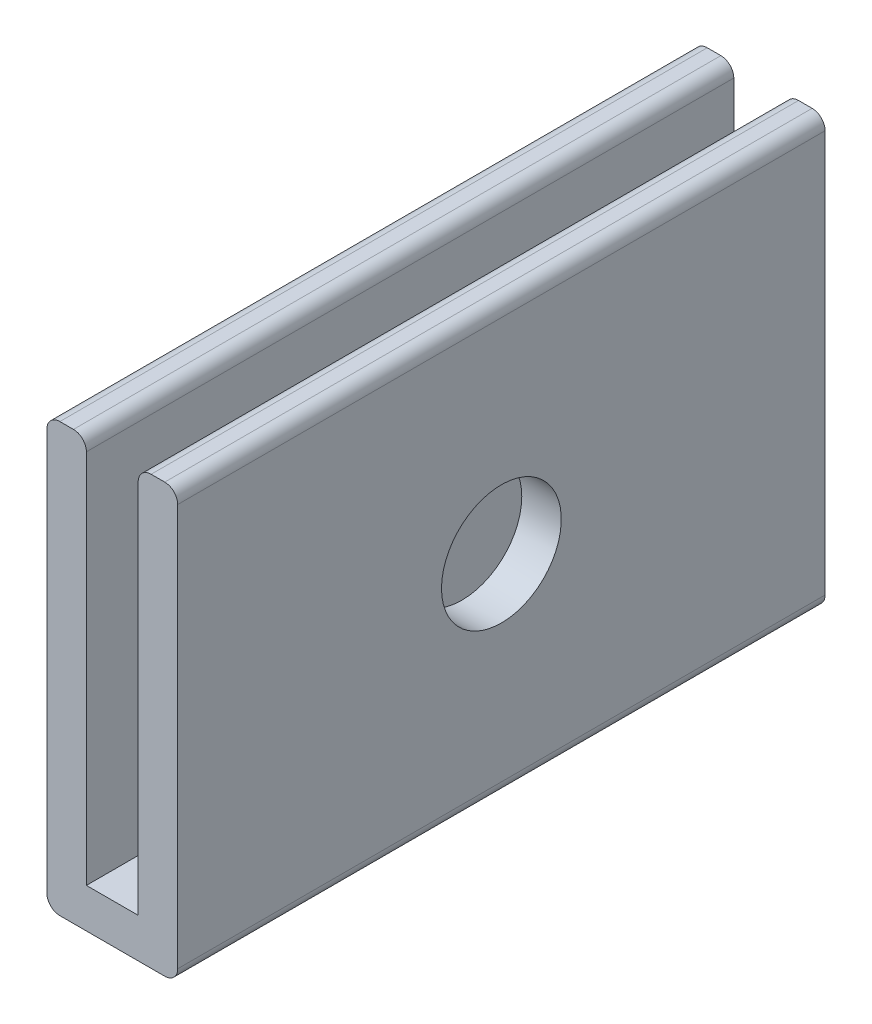
SolidWorks part; units mm, degrees
ref_plane "Front Plane" through (0, 0, 0) normal (0, 0, 1) x (1, 0, 0)
ref_plane "Top Plane" through (0, 0, 0) normal (0, 1, 0) x (1, 0, 0)
ref_plane "Right Plane" through (0, 0, 0) normal (1, 0, 0) x (0, 0, -1)
sketch "Sketch1" plane through (0, 0, 0) normal (0, 0, 1) x (1, 0, 0)
  line L17 (3.22, 13.22) -> (3.64, 13.22)
  line L18 (1.22, 1.22) -> (2.82, 1.22)
  line L19 (0.4, 0) -> (3.64, 0)
  line L20 (0, 0.4) -> (0, 12.82)
  line L21 (0.4, 13.22) -> (0.82, 13.22)
  line L22 (4.04, 0.4) -> (4.04, 12.82)
  line L27 (1.22, 1.22) -> (1.22, 12.82)
  line L29 (2.82, 1.22) -> (2.82, 12.82)
  arc A12 (3.64, 13.22) -> (4.04, 12.82) centre (3.64, 12.82) cw
  arc A13 (3.22, 13.22) -> (2.82, 12.82) centre (3.22, 12.82) ccw
  arc A14 (1.22, 12.82) -> (0.82, 13.22) centre (0.82, 12.82) ccw
  arc A15 (0, 12.82) -> (0.4, 13.22) centre (0.4, 12.82) cw
  arc A16 (3.64, 0) -> (4.04, 0.4) centre (3.64, 0.4) ccw
  arc A17 (0.4, 0) -> (0, 0.4) centre (0.4, 0.4) cw
extrude "Boss-Extrude1" add sketch "Sketch1" along normal blind 20
sketch "Sketch2" plane through (0, 0, 0) normal (-1, 0, 0) x (0, 0, 1)
  circle A0 centre (10, 6.5) radius 1.85
extrude "Cut-Extrude1" cut sketch "Sketch2" against normal up to surface (4.04 mm away) up to face at (4.04, 6.61, 10)
